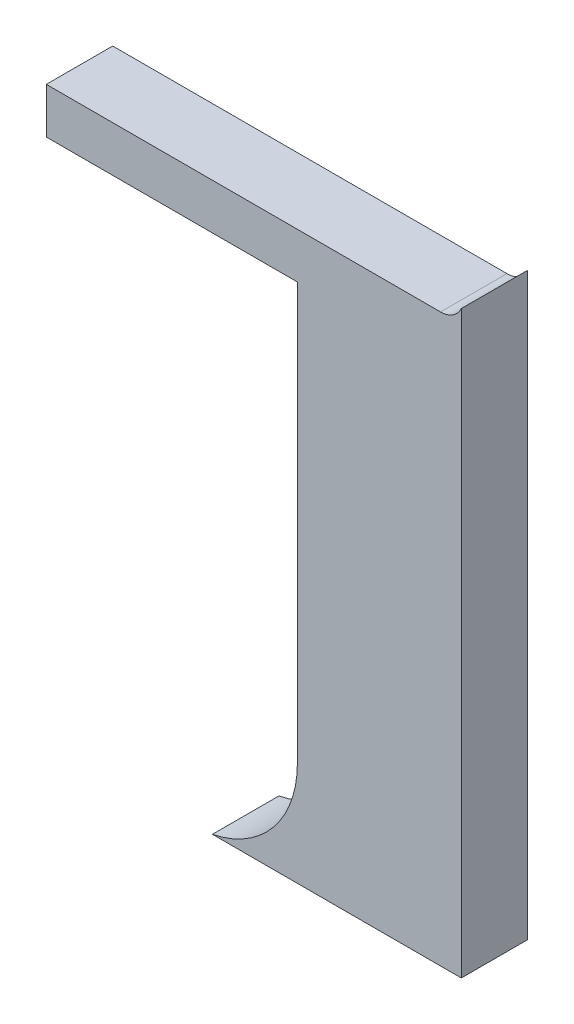
SolidWorks part; units mm, degrees
material "PET"
ref_plane "Piano frontale" through (0, 0, 0) normal (0, 0, 1) x (1, 0, 0)
ref_plane "Piano superiore" through (0, 0, 0) normal (0, 1, 0) x (1, 0, 0)
ref_plane "Piano destro" through (0, 0, 0) normal (1, 0, 0) x (0, 0, -1)
sketch "Schizzo1" plane through (0, 0, 0) normal (0, 0, 1) x (1, 0, 0)
  line L0 (23.5106, -46.7) -> (37, -46.7) construction
  line L1 (41.9, -41.8) -> (41.9, -13.8) construction
  line L2 (37, -8.9) -> (37, -7.9) construction
  line L3 (42.9, -13.8) -> (42.9, -41.8) construction
  line L4 (37, -47.7) -> (-7, -47.7) construction
  line L5 (-7, -47.7) -> (-7, -57.8) construction
  line L6 (-7, -57.8) -> (43, -57.8) construction
  line L7 (53, -47.8) -> (53, -7.8) construction
  line L8 (53, -7.8) -> (10.4881, -7.8) construction
  line L9 (10.4881, -7.8) -> (10.4881, -15.8) construction
  line L10 (10.4881, -15.8) -> (8.4705, -15.8) construction
  line L11 (8.4705, -15.8) -> (8.4705, -21.8) construction
  line L12 (8.4705, -21.8) -> (12.4924, -21.8) construction
  line L13 (23.5106, -39.8892) -> (23.5106, -46.7) construction
  line L14 (56.5303, 26) -> (36.167, 26) construction
  line L15 (36.167, 26) -> (36.167, 6) construction
  line L16 (36.167, 6) -> (56.5303, 6) construction
  line L17 (67, -3) -> (29, -3) construction
  line L18 (67, 33) -> (29, 33) construction
  line L19 (69, 31) -> (69, -1) construction
  line L20 (23.5106, -46.7) -> (37, -46.7)
  line L21 (41.9, -41.8) -> (41.9, -13.8)
  line L22 (37, -8.9) -> (37, -7.9)
  line L23 (42.9, -13.8) -> (42.9, -41.8)
  line L24 (37, -47.7) -> (-7, -47.7)
  line L25 (-7, -47.7) -> (-7, -57.8)
  line L26 (-7, -57.8) -> (43, -57.8)
  line L27 (53, -47.8) -> (53, -7.8)
  line L28 (53, -7.8) -> (10.4881, -7.8)
  line L29 (10.4881, -7.8) -> (10.4881, -15.8)
  line L30 (10.4881, -15.8) -> (8.4705, -15.8)
  line L31 (8.4705, -15.8) -> (8.4705, -21.8)
  line L32 (8.4705, -21.8) -> (12.4924, -21.8)
  line L33 (23.5106, -39.8892) -> (23.5106, -46.7)
  line L34 (56.5303, 26) -> (36.167, 26)
  line L35 (36.167, 26) -> (36.167, 6)
  line L36 (36.167, 6) -> (56.5303, 6)
  line L37 (67, -3) -> (29, -3)
  line L38 (67, 33) -> (29, 33)
  line L39 (69, 31) -> (69, -1)
  line L40 (53.2, -47.8) -> (53.2, -7.6)
  line L41 (29, 33) -> (69, 33)
  line L42 (29, 33) -> (29, -57.8)
  line L43 (29, -57.8) -> (69, -57.8)
  line L44 (69, 33) -> (69, -57.8)
  line L45 (53.2, -7.6) -> (10.2881, -7.6)
  line L46 (10.2881, -7.6) -> (10.2881, -15.6)
  line L47 (10.2881, -15.6) -> (8.2705, -15.6)
  line L48 (8.2705, -15.6) -> (8.2705, -22)
  line L49 (8.2705, -22) -> (12.6091, -22)
  line L50 (23.3106, -39.6959) -> (23.3106, -46.9)
  line L51 (23.3106, -46.9) -> (37, -46.9)
  line L52 (42.1, -41.8) -> (42.1, -13.8)
  line L53 (37.2, -8.7039) -> (37.2, -8.1035)
  line L54 (42.7, -13.8) -> (42.7, -41.8)
  line L55 (37, -47.5) -> (-7.2, -47.5)
  line L56 (-7.2, -47.5) -> (-7.2, -58)
  line L57 (-7.2, -58) -> (43, -58)
  line L58 (67, 33.2) -> (29, 33.2)
  line L59 (69.2, 31) -> (69.2, -1)
  line L60 (67, -3.2) -> (29, -3.2)
  arc A0 (37, -46.7) -> (41.9, -41.8) centre (37, -41.8) ccw construction
  arc A1 (41.9, -13.8) -> (37, -8.9) centre (37, -13.8) ccw construction
  arc A2 (42.9, -13.8) -> (37, -7.9) centre (37, -13.8) ccw construction
  arc A3 (37, -47.7) -> (42.9, -41.8) centre (37, -41.8) ccw construction
  arc A4 (43, -57.8) -> (53, -47.8) centre (43, -47.8) ccw construction
  arc A5 (23.5106, -39.8892) -> (12.4924, -21.8) centre (23, -27.8) ccw construction
  arc A6 (67, -3) -> (69, -1) centre (67, -1) ccw construction
  arc A7 (69, 31) -> (67, 33) centre (67, 31) ccw construction
  arc A8 (37, -46.7) -> (41.9, -41.8) centre (37, -41.8) ccw
  arc A9 (41.9, -13.8) -> (37, -8.9) centre (37, -13.8) ccw
  arc A10 (42.9, -13.8) -> (37, -7.9) centre (37, -13.8) ccw
  arc A11 (37, -47.7) -> (42.9, -41.8) centre (37, -41.8) ccw
  arc A12 (43, -57.8) -> (53, -47.8) centre (43, -47.8) ccw
  arc A13 (23.5106, -39.8892) -> (12.4924, -21.8) centre (23, -27.8) ccw
  arc A14 (67, -3) -> (69, -1) centre (67, -1) ccw
  arc A15 (69, 31) -> (67, 33) centre (67, 31) ccw
  arc A16 (23.3106, -39.6959) -> (12.6091, -22) centre (23, -27.8) ccw
  arc A17 (37, -46.9) -> (42.1, -41.8) centre (37, -41.8) ccw
  arc A18 (42.1, -13.8) -> (37.2, -8.7039) centre (37, -13.8) ccw
  arc A19 (42.7, -13.8) -> (37.2, -8.1035) centre (37, -13.8) ccw
  arc A20 (37, -47.5) -> (42.7, -41.8) centre (37, -41.8) ccw
  arc A21 (43, -58) -> (53.2, -47.8) centre (43, -47.8) ccw
  arc A22 (69.2, 31) -> (67, 33.2) centre (67, 31) ccw
  arc A23 (67, -3.2) -> (69.2, -1) centre (67, -1) ccw
  ellipse E0 centre (56.5303, 16) end of major axis (56.5303, 6) minor radius 9.9989 (56.5303, 6) -> (56.5303, 26) ccw construction
  ellipse E1 centre (56.5303, 16) end of major axis (56.5303, 6) minor radius 9.9989 (56.5303, 6) -> (56.5303, 26) ccw
  dimension "D1" = 0.2
  dimension "D2" = 0.2
extrude "Estrusione-Estrusione1" add sketch "Schizzo1" along normal up to vertex (6.4 mm away) contours A23 L60 L42 L45 L40 A21 L43 L44
